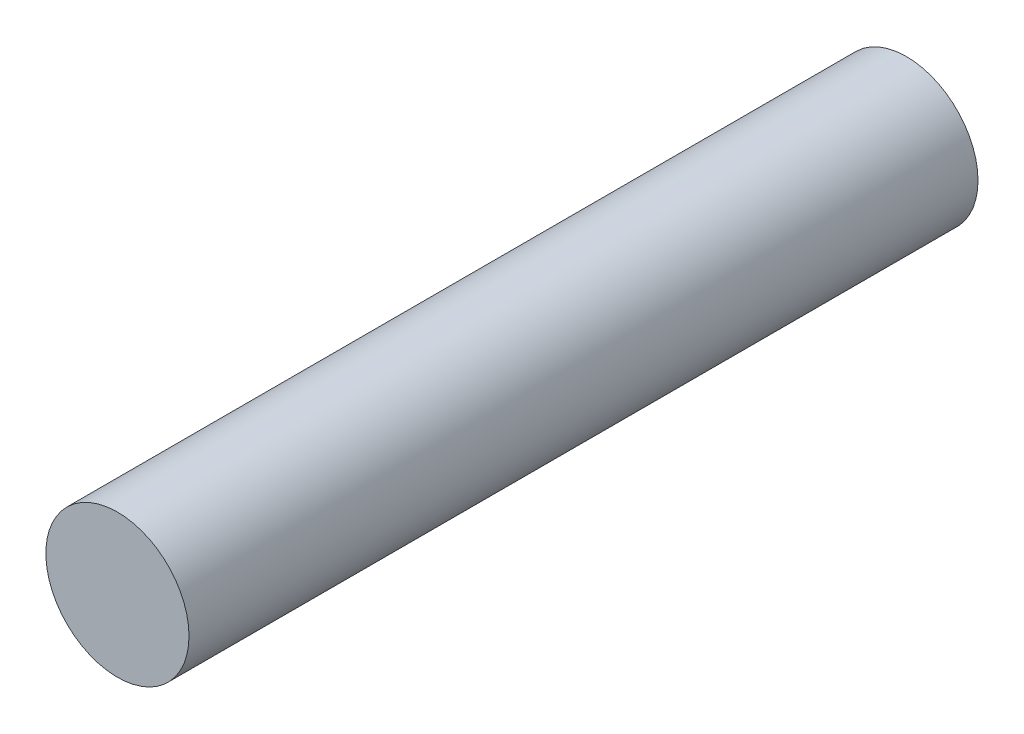
SolidWorks part; units mm, degrees
ref_plane "Front Plane" through (0, 0, 0) normal (0, 0, 1) x (1, 0, 0)
ref_plane "Top Plane" through (0, 0, 0) normal (0, 1, 0) x (1, 0, 0)
ref_plane "Right Plane" through (0, 0, 0) normal (1, 0, 0) x (0, 0, -1)
sketch "Sketch1" plane through (0, 0, 0) normal (0, 0, 1) x (1, 0, 0)
  circle A0 centre (0, 0) radius 6.35
  dimension "D1" = 12.7
extrude "Boss-Extrude1" add sketch "Sketch1" along normal mid plane 70 contours A0
